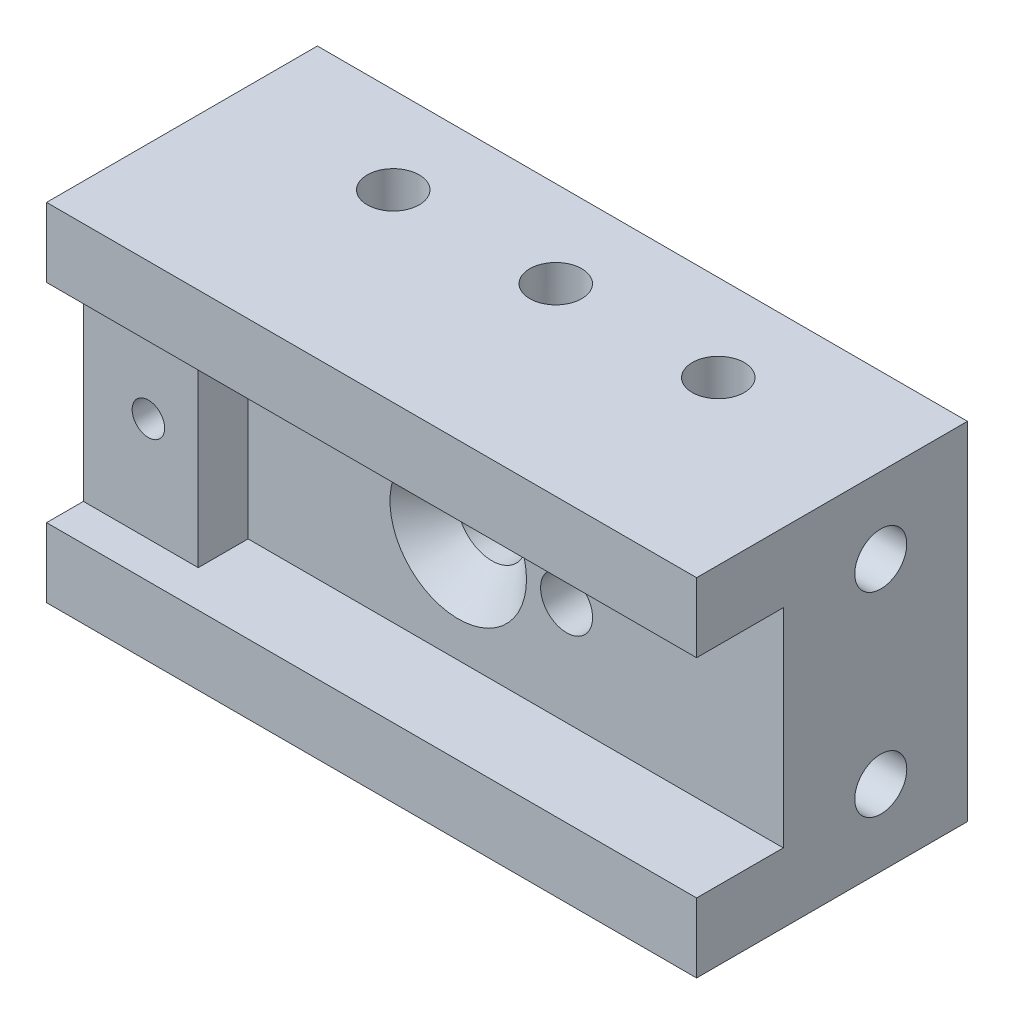
SolidWorks part; units mm, degrees
material "ABS"
ref_plane "Plan de face" through (0, 0, 0) normal (0, 0, 1) x (1, 0, 0)
ref_plane "Plan de dessus" through (0, 0, 0) normal (0, 1, 0) x (1, 0, 0)
ref_plane "Plan de droite" through (0, 0, 0) normal (1, 0, 0) x (0, 0, -1)
sketch "Esquisse1" plane through (0, 0, 0) normal (1, 0, 0) x (0, 0, -1)
  line L0 (-12.5, -4.8) -> (-12.5, -8)
  line L1 (-12.5, 8) -> (0, 8)
  line L2 (-12.5, 8) -> (-12.5, 4.8)
  line L3 (-12.5, -8) -> (0, -8)
  line L4 (0, 8) -> (0, -8)
  line L5 (-12.5, 4.8) -> (-8.5, 4.8)
  line L7 (-12.5, -4.8) -> (-8.5, -4.8)
  line L8 (-8.5, 4.8) -> (-8.5, -4.8)
  dimension "D1" = 9.6
  dimension "D2" = 4
  dimension "D3" = 16
  dimension "D4" = 8.5
extrude "Boss.-Extru.1" add sketch "Esquisse1" along normal mid plane 30
sketch "Esquisse2" plane through (0, 8, 0) normal (0, 1, 0) x (1, 0, 0)
  line L0 (0, 0) -> (0, -4) construction
  line L1 (15, 0) -> (-15, 0) construction
  circle A0 centre (-7.5, -4) radius 1.2
  circle A1 centre (7.5, -4) radius 1.2
  circle A2 centre (0, -4) radius 1.2
  dimension "D1" = 15
  dimension "D2" = 4
  dimension "D3" = 2.4
extrude "Enlèv. mat.-Extru.1" cut sketch "Esquisse2" against normal through all
sketch "Esquisse3" plane through (0, 0, 8.5) normal (0, 0, 1) x (1, 0, 0)
  line L1 (-15, 4.8) -> (-15, -4.8) construction
  circle A0 centre (-12, 0) radius 0.75
  point P9 (-15, 0)
  dimension "D1" = 1.5
  dimension "D2" = 3
extrude "Enlèv. mat.-Extru.2" cut sketch "Esquisse3" against normal through all
sketch "Esquisse4" plane through (15, 0, 0) normal (1, 0, 0) x (0, 0, -1)
  line L0 (0, 0) -> (-3.9845, 0) construction
  line L1 (0, -8) -> (0, 8) construction
  circle A0 centre (-4, -4.5) radius 1.2
  circle A1 centre (-4, 4.5) radius 1.2
  dimension "D1" = 2.4
  dimension "D2" = 9
  dimension "D3" = 4
extrude "Enlèv. mat.-Extru.3" cut sketch "Esquisse4" against normal through all
sketch "Esquisse5" plane through (0, 0, 8.5) normal (0, 0, 1) x (1, 0, 0)
  line L0 (15, 4.8) -> (-15, 4.8) construction
  line L1 (-15, -4.8) -> (-9.7, -4.8)
  line L2 (-15, -4.8) -> (-15, 4.8)
  line L3 (-15, 4.8) -> (-9.7, 4.8)
  line L4 (-9.7, -4.8) -> (-9.7, 4.8)
  circle A0 centre (-12, 0) radius 0.75 construction
  circle A1 centre (-12, 0) radius 0.75
  dimension "D1" = 5.3
extrude "Boss.-Extru.2" add sketch "Esquisse5" along normal blind 2.3
hole_wizard "Fraisage pour vis à tête fraisée M31" positions "Esquisse7" profile "Esquisse6" countersink size "M3" standard "Ansi Metric" end condition through all
sketch "Esquisse7" plane through (0, 0, 8.5) normal (0, 0, 1) x (1, 0, 0)
  point P0 (0, 0)
sketch "Esquisse6" plane through (0, 0, 8.5) normal (1, 0, 0) x (0, -1, 0)
  line L0 (0, 0) -> (0, 8.5)
  line L1 (0, 8.5) -> (1.6, 8.5)
  line L2 (1.6, 8.5) -> (1.6, 1.55)
  line L3 (1.6, 1.55) -> (3.15, 0)
  line L5 (3.15, 0) -> (0, 0)
  line L6 (-1.6, 1.55) -> (-3.15, 0) construction
  line L11 (0, -6.35) -> (0, 107.95) construction
  dimension "Diamètre du perçage jusqu'au prochain" = 3.2
  dimension "Profondeur du perçage jusqu'au prochain" = 8.5
  dimension "Diamètre du fraisage entrant" = 6.3
  dimension "Angle du fraisage entrant" = 90
sketch "Esquisse8" plane through (0, 0, 0) normal (0, 0, -1) x (-1, 0, 0)
  line L1 (14.8, 1.6166) -> (12, 3.2332)
  line L2 (12, 3.2332) -> (9.2, 1.6166)
  line L3 (9.2, 1.6166) -> (9.2, -1.6166)
  line L4 (9.2, -1.6166) -> (12, -3.2332)
  line L5 (12, -3.2332) -> (14.8, -1.6166)
  line L6 (14.8, -1.6166) -> (14.8, 1.6166)
  circle A0 centre (12, 0) radius 2.8 construction
  dimension "D1" = 5.6
extrude "Enlèv. mat.-Extru.4" cut sketch "Esquisse8" against normal blind 2.3
sketch "Esquisse9" plane through (0, 0, 8.5) normal (0, 0, 1) x (1, 0, 0)
  circle A0 centre (5, 0) radius 1.2
  dimension "D1" = 5
  dimension "D2" = 2.4
extrude "Enlèv. mat.-Extru.5" cut sketch "Esquisse9" against normal through all
